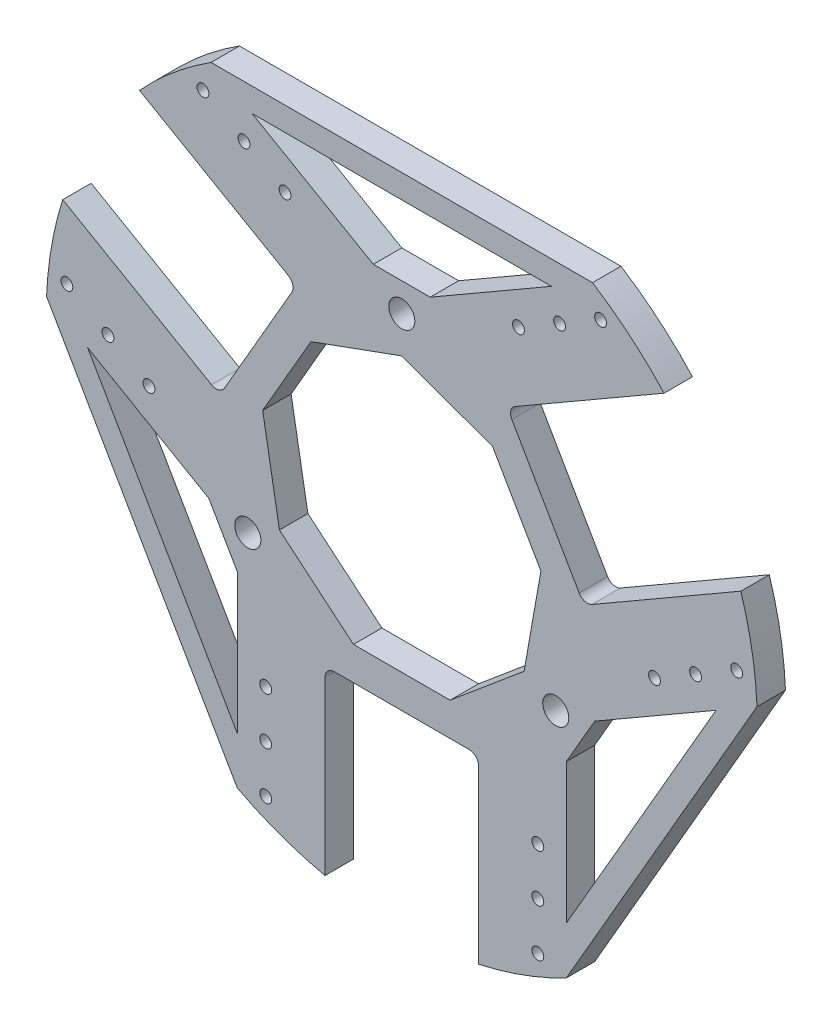
SolidWorks part; units mm, degrees
ref_plane "前视基准面" through (0, 0, 0) normal (0, 0, 1) x (1, 0, 0)
ref_plane "上视基准面" through (0, 0, 0) normal (0, 1, 0) x (1, 0, 0)
ref_plane "右视基准面" through (0, 0, 0) normal (1, 0, 0) x (0, 0, -1)
other "Configuration Table"
sketch "草图1" plane through (0, 0, 0) normal (0, 0, 1) x (1, 0, 0)
  line L0 (0, 0) -> (0, -75) construction
  line L1 (0, 0) -> (-64.9519, 37.5) construction
  line L2 (0, 0) -> (64.9519, 37.5) construction
  line L3 (28.7, -65) -> (28.7, -55) construction
  line L4 (-28.7, -65) -> (-28.7, -55) construction
  circle A0 centre (0, 0) radius 75
  circle A1 centre (28.7, -65) radius 1.25
  circle A2 centre (28.7, -55) radius 1.25
  circle A3 centre (28.7, -45) radius 1.25
  circle A4 centre (-28.7, -45) radius 1.25
  circle A5 centre (-28.7, -55) radius 1.25
  circle A6 centre (-28.7, -65) radius 1.25
  circle A7 centre (-24.6211, 47.3549) radius 1.25
  circle A8 centre (-33.2814, 52.3549) radius 1.25
  circle A9 centre (-41.9417, 57.3549) radius 1.25
  circle A10 centre (-53.3211, -2.3549) radius 1.25
  circle A11 centre (-61.9814, 2.6451) radius 1.25
  circle A12 centre (-70.6417, 7.6451) radius 1.25
  circle A13 centre (53.3211, -2.3549) radius 1.25
  circle A14 centre (61.9814, 2.6451) radius 1.25
  circle A15 centre (70.6417, 7.6451) radius 1.25
  circle A16 centre (24.6211, 47.3549) radius 1.25
  circle A17 centre (33.2814, 52.3549) radius 1.25
  circle A18 centre (41.9417, 57.3549) radius 1.25
  point P8 (0, 0)
  point P47 (0, 0)
  dimension "D1" = 150
  dimension "D3" = 2.5
  dimension "D4" = 28.7
  dimension "D7" = 45
  dimension "D6" = 10
  dimension "D5" = 3
  dimension "D2" = 3
  dimension "D8" = 3
extrude "凸台-拉伸1" add sketch "草图1" along normal blind 6
sketch "草图3" plane through (0, 0, 6) normal (0, 0, 1) x (1, 0, 0)
  line L0 (0, 0) -> (0, -75) construction
  line L1 (16.2, -37) -> (16.2, -73.2295)
  line L2 (14.2, -35) -> (-14.2, -35)
  line L3 (-16.2, -37) -> (-16.2, -73.2295)
  line L4 (-23.9429, 32.5296) -> (-55.3186, 50.6444)
  line L5 (-37.4109, 5.2024) -> (-23.2109, 29.7976)
  line L6 (-40.1429, 4.4704) -> (-71.5186, 22.5851)
  line L7 (40.1429, 4.4704) -> (71.5186, 22.5851)
  line L8 (23.2109, 29.7976) -> (37.4109, 5.2024)
  line L9 (23.9429, 32.5296) -> (55.3186, 50.6444)
  circle A0 centre (0, 0) radius 75 construction
  circle A2 centre (28.7, -45) radius 1.25 construction
  arc A3 (16.2, -37) -> (14.2, -35) centre (14.2, -37) ccw
  arc A4 (-16.2, -73.2295) -> (16.2, -73.2295) centre (0, 0) ccw
  arc A5 (-16.2, -37) -> (-14.2, -35) centre (-14.2, -37) cw
  arc A6 (-23.9429, 32.5296) -> (-23.2109, 29.7976) centre (-24.9429, 30.7976) cw
  arc A7 (-40.1429, 4.4704) -> (-37.4109, 5.2024) centre (-39.1429, 6.2024) ccw
  arc A8 (40.1429, 4.4704) -> (37.4109, 5.2024) centre (39.1429, 6.2024) cw
  arc A9 (23.9429, 32.5296) -> (23.2109, 29.7976) centre (24.9429, 30.7976) ccw
  arc A10 (-55.3186, 50.6444) -> (-71.5186, 22.5851) centre (0, 0) ccw
  arc A11 (71.5186, 22.5851) -> (55.3186, 50.6444) centre (0, 0) ccw
  point P17 (0, -35)
  point P36 (0, 0)
  dimension "D3" = 2
  dimension "D1" = 16.2
  dimension "D2" = 10
  dimension "D4" = 3
extrude "切除-拉伸2" cut sketch "草图3" against normal blind 10
sketch "草图5" plane through (0, 0, 6) normal (0, 0, 1) x (1, 0, 0)
  line L0 (-40.232, 63.296) -> (-6, 43.5322)
  line L1 (-6, 43.5322) -> (6, 43.5322)
  line L2 (-23.9429, 32.5296) -> (-55.3186, 50.6444) construction
  line L3 (0, 0) -> (0, 75) construction
  line L4 (40.232, 63.296) -> (6, 43.5322)
  line L5 (74.932, 3.1939) -> (40.7, -16.57)
  line L6 (34.7, -66.4899) -> (34.7, -26.9623)
  line L7 (40.7, -16.57) -> (34.7, -26.9623)
  line L8 (-34.7, -66.4899) -> (-34.7, -26.9623)
  line L9 (-74.932, 3.1939) -> (-40.7, -16.57)
  line L10 (-34.7, -26.9623) -> (-40.7, -16.57)
  arc A0 (55.3186, 50.6444) -> (-55.3186, 50.6444) centre (0, 0) ccw construction
  circle A1 centre (-33.2814, 52.3549) radius 1.25 construction
  arc A2 (40.232, 63.296) -> (-40.232, 63.296) centre (0, 0) ccw
  arc A3 (34.7, -66.4899) -> (74.932, 3.1939) centre (0, 0) ccw
  arc A4 (-74.932, 3.1939) -> (-34.7, -66.4899) centre (0, 0) ccw
  point P14 (0, 43.5322)
  point P25 (0, 0)
  dimension "D1" = 6
  dimension "D2" = 6
  dimension "D3" = 3
extrude "切除-拉伸3" cut sketch "草图5" against normal blind 10
sketch "草图6" plane through (0, 0, 6) normal (0, 0, 1) x (1, 0, 0)
  line L0 (-74.932, 3.1939) -> (-34.7, -66.4899)
  line L1 (-34.7, -66.4899) -> (-34.7, -56.4899)
  line L2 (-34.7, -66.4899) -> (-34.7, -26.9623) construction
  line L3 (-34.7, -56.4899) -> (-66.2717, -1.8061)
  line L4 (-40.7, -16.57) -> (-74.932, 3.1939) construction
  line L5 (-66.2717, -1.8061) -> (-74.932, 3.1939)
  line L6 (31.5717, 58.296) -> (40.232, 63.296)
  line L7 (-31.5717, 58.296) -> (31.5717, 58.296)
  line L8 (40.232, 63.296) -> (-40.232, 63.296)
  line L9 (-40.232, 63.296) -> (-31.5717, 58.296)
  line L10 (34.7, -56.4899) -> (34.7, -66.4899)
  line L11 (66.2717, -1.8061) -> (34.7, -56.4899)
  line L12 (34.7, -66.4899) -> (74.932, 3.1939)
  line L13 (74.932, 3.1939) -> (66.2717, -1.8061)
  point P20 (0, 0)
  dimension "D1" = 5
  dimension "D2" = 3
extrude "凸台-拉伸2" add sketch "草图6" against normal blind 6
sketch "草图7" plane through (0, 0, 6) normal (0, 0, 1) x (1, 0, 0)
  line L0 (14.2, -35) -> (-14.2, -35) construction
  line L1 (-25.8049, -14.8985) -> (-10.1912, -28)
  line L2 (-10.1912, -28) -> (10.1912, -28)
  line L3 (10.1912, -28) -> (25.8049, -14.8985)
  line L4 (25.8049, -14.8985) -> (29.3443, 5.1742)
  line L5 (29.3443, 5.1742) -> (19.1531, 22.8258)
  line L6 (19.1531, 22.8258) -> (0, 29.797)
  line L7 (0, 29.797) -> (-19.1531, 22.8258)
  line L8 (-19.1531, 22.8258) -> (-29.3443, 5.1742)
  line L9 (-29.3443, 5.1742) -> (-25.8049, -14.8985)
  circle A0 centre (0, 0) radius 28 construction
  dimension "D1" = 7
extrude "切除-拉伸4" cut sketch "草图7" against normal blind 6
sketch "草图8" plane through (0, 0, 6) normal (0, 0, 1) x (1, 0, 0)
  line L0 (0, 0) -> (0, 65.4003) construction
  circle A0 centre (0, 0) radius 37.5 construction
  circle A1 centre (0, 37.5) radius 2.75
  circle A2 centre (32.476, -18.75) radius 2.75
  circle A3 centre (-32.476, -18.75) radius 2.75
  point P12 (0, 0)
  dimension "D1" = 75
  dimension "D2" = 5.5
  dimension "D3" = 3
extrude "切除-拉伸5" cut sketch "草图8" against normal blind 10
